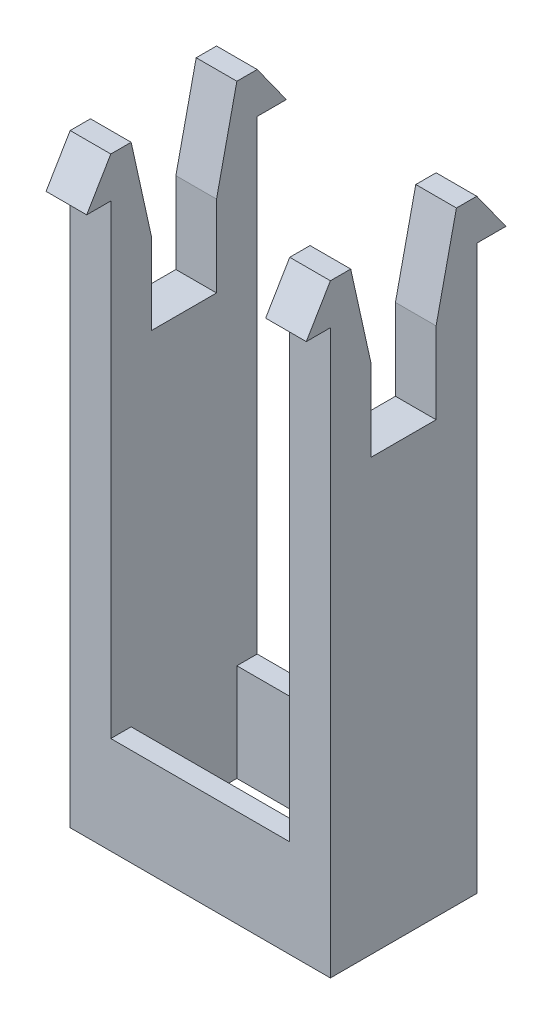
SolidWorks part; units mm, degrees
ref_plane "Front" through (0, 0, 0) normal (0, 0, 1) x (1, 0, 0)
ref_plane "Top" through (0, 0, 0) normal (0, 1, 0) x (1, 0, 0)
ref_plane "Right" through (0, 0, 0) normal (1, 0, 0) x (0, 0, -1)
sketch "Sketch1" plane through (0, 0, 0) normal (1, 0, 0) x (0, 0, -1)
  line L0 (-2.8076, 28.9828) -> (-1.0137, 26.4828)
  line L1 (-11.8076, -8.1422) -> (-2.8076, -8.1422)
  line L2 (-11.8076, -8.1422) -> (-11.8076, 23.3078)
  line L3 (-11.8076, 23.3078) -> (-2.8076, 23.3078)
  line L4 (-2.8076, -8.1422) -> (-2.8076, 23.3078)
  line L9 (-2.8076, 23.3078) -> (-5.3076, 23.3078)
  line L10 (-2.8076, 23.3078) -> (-2.8076, 28.9828)
  line L11 (-2.8076, 28.9828) -> (-5.3076, 28.9828)
  line L12 (-5.3076, 23.3078) -> (-5.3076, 28.9828)
  line L13 (-9.3076, 23.3078) -> (-11.8076, 23.3078)
  line L14 (-9.3076, 23.3078) -> (-9.3076, 28.9828)
  line L15 (-9.3076, 28.9828) -> (-11.8076, 28.9828)
  line L16 (-11.8076, 23.3078) -> (-11.8076, 28.9828)
  line L17 (-1.0137, 26.4828) -> (-2.8076, 26.4828)
  line L18 (-11.8076, 28.9828) -> (-13.2888, 26.4828)
  line L19 (-13.2888, 26.4828) -> (-11.8076, 26.4828)
  line L20 (-4.0576, 28.9828) -> (-5.3076, 23.3328)
  line L21 (-10.5576, 28.9828) -> (-9.3076, 23.3328)
  dimension "D1" = 9
  dimension "D2" = 2.5
  dimension "D3" = 2.5
  dimension "D4" = 5.675
  dimension "D5" = 2.5
  dimension "D6" = 2.5
  dimension "D7" = 31.45
extrude "Boss-Extrude1" add sketch "Sketch1" against normal blind 16 contours L17 L0 L10 | L11 L20 L12 L3 L10 | L21 L15 L16 L3 L14 | L18 L19 L16 | L1 L4 L3 L2
sketch "Sketch2" plane through (0, 0, 11.8076) normal (0, 0, 1) x (1, 0, 0)
  line L0 (-16, 28.9828) -> (0, 28.9828) construction
  line L1 (-13.5, 28.9828) -> (-2.5, 28.9828)
  line L2 (-13.5, 28.9828) -> (-13.5, -2.1422)
  line L3 (-13.5, -2.1422) -> (-2.5, -2.1422)
  line L4 (-2.5, 28.9828) -> (-2.5, -2.1422)
  line L5 (-16, -8.1422) -> (0, -8.1422) construction
  line L6 (-16, -8.1422) -> (-16, 26.4828) construction
  dimension "D1" = 6
  dimension "D2" = 11
  dimension "D3" = 2.5
extrude "Cut-Extrude1" cut sketch "Sketch2" against normal through all both and the other way through all
sketch "Sketch3" plane through (0, 0, 0) normal (1, 0, 0) x (0, 0, -1)
  line L1 (-9.3076, 23.3328) -> (-5.3076, 23.3328)
  line L2 (-9.3076, 23.3328) -> (-9.3076, 18.3328)
  line L3 (-9.3076, 18.3328) -> (-5.3076, 18.3328)
  line L4 (-5.3076, 23.3328) -> (-5.3076, 18.3328)
  dimension "D1" = 5
extrude "Cut-Extrude2" cut sketch "Sketch3" against normal through all both and the other way through all
sketch "Sketch4" plane through (0, -2.1422, 0) normal (0, 1, 0) x (1, 0, 0)
  line L0 (-2.5, -2.8076) -> (-2.5, -4.0576) construction
  line L1 (-13.5, -10.5576) -> (-2.5, -10.5576)
  line L2 (-13.5, -10.5576) -> (-13.5, -4.0576)
  line L3 (-13.5, -4.0576) -> (-2.5, -4.0576)
  line L4 (-2.5, -10.5576) -> (-2.5, -4.0576)
  line L5 (-2.5, -2.8076) -> (-2.5, -11.8076) construction
extrude "Cut-Extrude3" cut sketch "Sketch4" against normal through all
